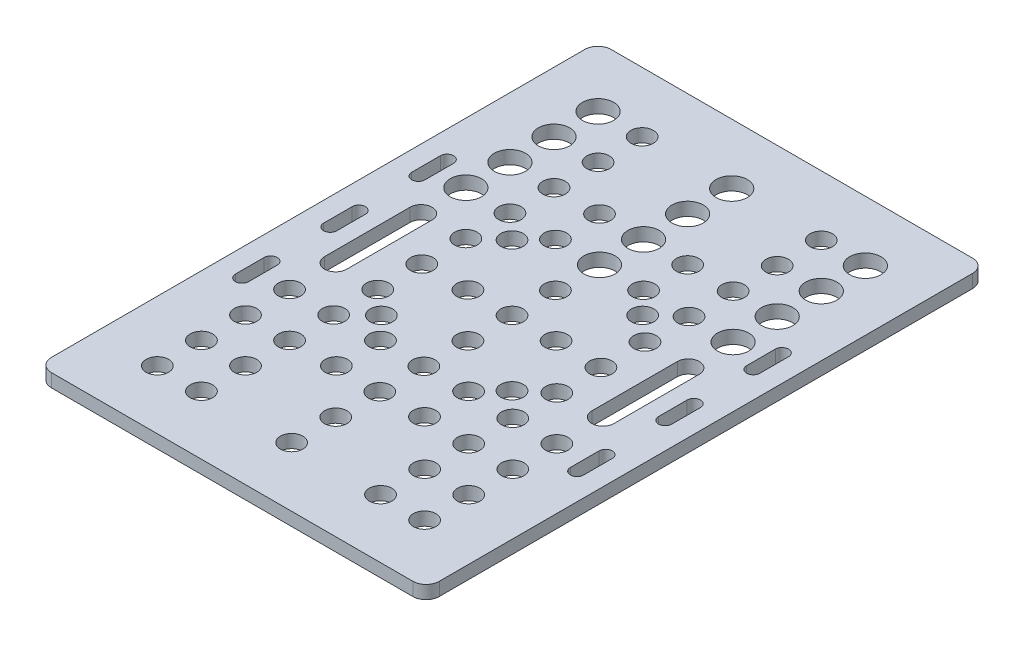
SolidWorks part; units mm, degrees
material "氧化铝"
ref_plane "前视基准面" through (0, 0, 0) normal (0, 0, 1) x (1, 0, 0)
ref_plane "上视基准面" through (0, 0, 0) normal (0, 1, 0) x (1, 0, 0)
ref_plane "右视基准面" through (0, 0, 0) normal (1, 0, 0) x (0, 0, -1)
other "Configuration Table"
sketch "草图1" plane through (0, 0, 0) normal (0, 1, 0) x (1, 0, 0)
  line L0 (44, 59.9931) -> (44, -145.8087) construction
  line L1 (0, 0) -> (88, 0)
  line L2 (0, 0) -> (0, -127)
  line L3 (0, -127) -> (88, -127)
  line L4 (88, 0) -> (88, -127)
  line L5 (-69.4798, -63.5) -> (172.0857, -63.5) construction
  line L6 (13.68, -13.65) -> (44, -13.65) construction
  line L7 (13.68, -13.65) -> (13.68, -23.65) construction
  line L8 (23.68, -13.65) -> (23.68, -23.65) construction
  line L9 (44, -63.5) -> (44, -73.5) construction
  line L10 (13.68, -83.65) -> (13.68, -93.65) construction
  line L11 (6, -40.25) -> (6, -46.75) construction
  line L12 (7.5, -40.25) -> (7.5, -46.75)
  line L13 (4.5, -40.25) -> (4.5, -46.75)
  line L14 (6, -60.25) -> (6, -66.75) construction
  line L15 (7.5, -60.25) -> (7.5, -66.75)
  line L16 (4.5, -60.25) -> (4.5, -66.75)
  line L17 (6, -86.75) -> (6, -80.25) construction
  line L18 (7.5, -86.75) -> (7.5, -80.25)
  line L19 (4.5, -86.75) -> (4.5, -80.25)
  line L20 (82, -86.75) -> (82, -80.25) construction
  line L21 (80.5, -86.75) -> (80.5, -80.25)
  line L22 (83.5, -86.75) -> (83.5, -80.25)
  line L23 (82, -60.25) -> (82, -66.75) construction
  line L24 (80.5, -60.25) -> (80.5, -66.75)
  line L25 (83.5, -60.25) -> (83.5, -66.75)
  line L26 (82, -40.25) -> (82, -46.75) construction
  line L27 (80.5, -40.25) -> (80.5, -46.75)
  line L28 (83.5, -40.25) -> (83.5, -46.75)
  line L29 (13.68, -53.81) -> (13.68, -73.19) construction
  line L30 (16.18, -53.81) -> (16.18, -73.19)
  line L31 (11.18, -53.81) -> (11.18, -73.19)
  line L32 (74.32, -53.81) -> (74.32, -73.19) construction
  line L33 (71.82, -53.81) -> (71.82, -73.19)
  line L34 (76.82, -53.81) -> (76.82, -73.19)
  circle A0 centre (13.68, -13.65) radius 3.55
  circle A1 centre (44, -13.65) radius 3.55
  circle A2 centre (74.32, -13.65) radius 3.55
  circle A3 centre (44, -23.65) radius 3.55
  circle A4 centre (74.32, -23.65) radius 3.55
  circle A5 centre (44, -33.65) radius 3.55
  circle A6 centre (74.32, -33.65) radius 3.55
  circle A7 centre (44, -43.65) radius 3.55
  circle A8 centre (74.32, -43.65) radius 3.55
  circle A9 centre (13.68, -23.65) radius 3.55
  circle A10 centre (13.68, -33.65) radius 3.55
  circle A11 centre (13.68, -43.65) radius 3.55
  circle A12 centre (23.68, -13.65) radius 2.55
  circle A13 centre (64.32, -13.65) radius 2.55
  circle A14 centre (23.68, -23.65) radius 2.55
  circle A15 centre (64.32, -23.65) radius 2.55
  circle A16 centre (23.68, -33.65) radius 2.55
  circle A17 centre (64.32, -33.65) radius 2.55
  circle A18 centre (23.68, -43.65) radius 2.55
  circle A19 centre (64.32, -43.65) radius 2.55
  circle A20 centre (23.68, -53.65) radius 2.55
  circle A21 centre (64.32, -53.65) radius 2.55
  circle A22 centre (23.68, -63.65) radius 2.55
  circle A23 centre (64.32, -63.65) radius 2.55
  circle A24 centre (23.68, -73.65) radius 2.55
  circle A25 centre (64.32, -73.65) radius 2.55
  circle A26 centre (23.68, -83.65) radius 2.55
  circle A27 centre (64.32, -83.65) radius 2.55
  circle A28 centre (23.68, -93.65) radius 2.55
  circle A29 centre (64.32, -93.65) radius 2.55
  circle A30 centre (23.68, -103.65) radius 2.55
  circle A31 centre (64.32, -103.65) radius 2.55
  circle A32 centre (23.68, -113.65) radius 2.55
  circle A33 centre (64.32, -113.65) radius 2.55
  circle A34 centre (29.18, -48.68) radius 2.55
  circle A35 centre (29.18, -78.32) radius 2.55
  circle A36 centre (58.82, -48.68) radius 2.55
  circle A37 centre (58.82, -78.32) radius 2.55
  circle A38 centre (34, -63.5) radius 2.55
  circle A39 centre (54, -63.5) radius 2.55
  circle A40 centre (44, -63.5) radius 2.55
  circle A41 centre (34, -33.65) radius 2.55
  circle A42 centre (34, -43.65) radius 2.55
  circle A43 centre (54, -43.65) radius 2.55
  circle A44 centre (54, -33.65) radius 2.55
  circle A45 centre (54, -93.35) radius 2.55
  circle A46 centre (54, -83.35) radius 2.55
  circle A47 centre (34, -83.35) radius 2.55
  circle A48 centre (34, -93.35) radius 2.55
  circle A49 centre (44, -53.65) radius 2.55
  circle A50 centre (44, -73.5) radius 2.55
  circle A51 centre (44, -83.5) radius 2.55
  circle A52 centre (44, -93.5) radius 2.55
  circle A53 centre (44, -103.5) radius 2.55
  circle A54 centre (44, -113.5) radius 2.55
  circle A55 centre (13.68, -83.65) radius 2.55
  circle A56 centre (74.32, -83.65) radius 2.55
  circle A57 centre (13.68, -93.65) radius 2.55
  circle A58 centre (74.32, -93.65) radius 2.55
  circle A59 centre (13.68, -103.65) radius 2.55
  circle A60 centre (74.32, -103.65) radius 2.55
  circle A61 centre (13.68, -113.65) radius 2.55
  circle A62 centre (74.32, -113.65) radius 2.55
  arc A63 (7.5, -40.25) -> (4.5, -40.25) centre (6, -40.25) ccw
  arc A64 (4.5, -46.75) -> (7.5, -46.75) centre (6, -46.75) ccw
  arc A65 (7.5, -60.25) -> (4.5, -60.25) centre (6, -60.25) ccw
  arc A66 (4.5, -66.75) -> (7.5, -66.75) centre (6, -66.75) ccw
  arc A67 (7.5, -86.75) -> (4.5, -86.75) centre (6, -86.75) cw
  arc A68 (4.5, -80.25) -> (7.5, -80.25) centre (6, -80.25) cw
  arc A69 (80.5, -86.75) -> (83.5, -86.75) centre (82, -86.75) ccw
  arc A70 (83.5, -80.25) -> (80.5, -80.25) centre (82, -80.25) ccw
  arc A71 (80.5, -60.25) -> (83.5, -60.25) centre (82, -60.25) cw
  arc A72 (83.5, -66.75) -> (80.5, -66.75) centre (82, -66.75) cw
  arc A73 (80.5, -40.25) -> (83.5, -40.25) centre (82, -40.25) cw
  arc A74 (83.5, -46.75) -> (80.5, -46.75) centre (82, -46.75) cw
  arc A75 (16.18, -53.81) -> (11.18, -53.81) centre (13.68, -53.81) ccw
  arc A76 (11.18, -73.19) -> (16.18, -73.19) centre (13.68, -73.19) ccw
  arc A77 (71.82, -53.81) -> (76.82, -53.81) centre (74.32, -53.81) cw
  arc A78 (76.82, -73.19) -> (71.82, -73.19) centre (74.32, -73.19) cw
  point P146 (6, -43.5)
  point P151 (6, -63.5)
  point P158 (13.68, -63.5)
  point P162 (6, -83.5)
  point P169 (82, -83.5)
  point P176 (82, -63.5)
  point P183 (82, -43.5)
  point P193 (0, 0)
  point P194 (0, 0)
  point P195 (0, 0)
  point P196 (0, 0)
  point P199 (74.32, -63.5)
  dimension "D5" = 7.1
  dimension "D11" = 5.1
  dimension "D1" = 88
  dimension "D2" = 127
  dimension "D3" = 44
  dimension "D4" = 63.5
  dimension "D8" = 30.32
  dimension "D9" = 10
  dimension "D10" = 13.65
  dimension "D12" = 10
  dimension "D14" = 10
  dimension "D15" = 29.18
  dimension "D16" = 48.68
  dimension "D17" = 34
  dimension "D19" = 10
  dimension "D21" = 10
  dimension "D22" = 6
  dimension "D23" = 3
  dimension "D24" = 40.25
  dimension "D25" = 46.75
  dimension "D26" = 6.5
  dimension "D27" = 5
  dimension "D28" = 53.81
  dimension "D6" = 3
  dimension "D7" = 4
  dimension "D13" = 11
  dimension "D18" = 6
  dimension "D20" = 4
extrude "凸台-拉伸1" add sketch "草图1" along normal blind 3
fillet "圆角1" radius 3 4 edges at (0, 1.5, 127) (88, 1.5, 127) (88, 1.5, 0) (0, 1.5, 0)
